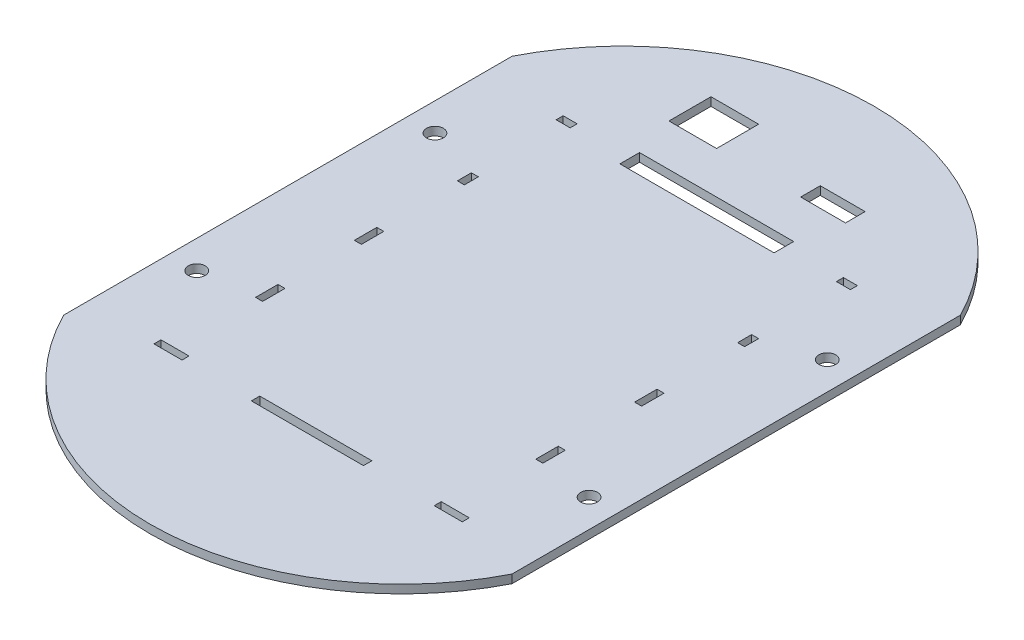
SolidWorks part; units mm, degrees
ref_plane "Front Plane" through (0, 0, 0) normal (0, 0, 1) x (1, 0, 0)
ref_plane "Top Plane" through (0, 0, 0) normal (0, 1, 0) x (1, 0, 0)
ref_plane "Right Plane" through (0, 0, 0) normal (1, 0, 0) x (0, 0, -1)
sketch "Sketch1" plane through (0, 0, 0) normal (0, 1, 0) x (1, 0, 0)
  line L0 (0, 80) -> (191.8529, 80) construction
  line L6 (0, 0) -> (0, 160)
  line L8 (160, 0) -> (160, 160)
  arc A2 (0, 160) -> (160, 160) centre (80, 119.5198) cw
  arc A3 (0, 160) -> (160, 160) centre (80, 160) cw construction
  arc A4 (0, 0) -> (160, 0) centre (80, 40.4802) ccw
  dimension "D3" = 89.6585
  dimension "D1" = 160
  dimension "D2" = 160
extrude "Boss-Extrude1" add sketch "Sketch1" along normal blind 3
sketch "Sketch5" plane through (0, 3, 0) normal (0, 1, 0) x (1, 0, 0)
  line L0 (0, 80) -> (201.3848, 80) construction
  line L1 (0, 160) -> (0, 0) construction
  line L2 (80, 209.1783) -> (80, -99.5859) construction
  circle A0 centre (10, 37.5) radius 3
  arc A1 (160, 160) -> (0, 160) centre (80, 119.5198) ccw construction
  circle A2 centre (150, 37.5) radius 3
  circle A3 centre (150, 122.5) radius 3
  circle A4 centre (10, 122.5) radius 3
  dimension "D1" = 37.5
  dimension "D3" = 6
  dimension "D2" = 10
extrude "Cut-Extrude2" cut sketch "Sketch5" against normal blind 44
sketch "Sketch6" plane through (0, 3, 0) normal (0, 1, 0) x (1, 0, 0)
  line L0 (10, 46.3052) -> (10, 3.8665) construction
  line L1 (150, 150.6243) -> (150, -5.6642) construction
  line L2 (155.6387, 37.5) -> (145.0603, 37.5) construction
  circle A0 centre (9.8857, 144.5) radius 3
  circle A1 centre (9.8857, 122.5) radius 3
  circle A2 centre (10, 122.5) radius 3 construction
  circle A3 centre (150, 122.5) radius 3 construction
  circle A4 centre (10, 37.5) radius 3 construction
  circle A5 centre (150, 122.5) radius 3 construction
  circle A6 centre (10, 37.5) radius 3 construction
  circle A7 centre (10, 15.5) radius 3
  circle A10 centre (150, 144.5) radius 3
  circle A11 centre (150, 15.5) radius 3
  dimension "D1" = 6
  dimension "D2" = 6
  dimension "D5" = 22
  dimension "D6" = 6
  dimension "D7" = 6
  dimension "D10" = 6
  dimension "D3" = 0
  dimension "D4" = 22
  dimension "D8" = 22
  dimension "D9" = 22
sketch "Sketch8" plane through (0, 3, 0) normal (0, 1, 0) x (1, 0, 0)
  line L0 (0, 160) -> (0, 0) construction
  line L1 (52.5, 153) -> (107.5, 153)
  line L2 (52.5, 153) -> (52.5, 146)
  line L3 (52.5, 146) -> (107.5, 146)
  line L4 (107.5, 153) -> (107.5, 146)
  line L5 (52.5, 153) -> (107.5, 146) construction
  line L6 (52.5, 146) -> (107.5, 153) construction
  line L7 (28.75, 39.75) -> (31.25, 39.75)
  line L8 (60, 7) -> (100, 7)
  line L9 (60, 10) -> (100, 10)
  line L10 (100, 10) -> (100, 7)
  line L11 (60, 10) -> (100, 7) construction
  line L12 (60, 7) -> (100, 10) construction
  line L13 (60, 10) -> (60, 7)
  line L14 (30, 222.0853) -> (30, -127.904) construction
  line L15 (27.5, 150.75) -> (32.5, 150.75)
  line L16 (27.5, 150.75) -> (27.5, 148.25)
  line L17 (27.5, 148.25) -> (32.5, 148.25)
  line L18 (32.5, 150.75) -> (32.5, 148.25)
  line L19 (27.5, 150.75) -> (32.5, 148.25) construction
  line L20 (27.5, 148.25) -> (32.5, 150.75) construction
  line L21 (127.5, 150.75) -> (132.5, 150.75)
  line L22 (127.5, 150.75) -> (127.5, 148.25)
  line L23 (127.5, 148.25) -> (132.5, 148.25)
  line L24 (132.5, 150.75) -> (132.5, 148.25)
  line L25 (127.5, 150.75) -> (132.5, 148.25) construction
  line L26 (127.5, 148.25) -> (132.5, 150.75) construction
  line L31 (131.25, 111.75) -> (128.75, 111.75)
  line L32 (131.25, 111.75) -> (131.25, 116.75)
  line L33 (28.75, 116.75) -> (31.25, 116.75)
  line L34 (28.75, 116.75) -> (28.75, 111.75)
  line L35 (28.75, 111.75) -> (31.25, 111.75)
  line L36 (31.25, 116.75) -> (31.25, 111.75)
  line L37 (28.75, 116.75) -> (31.25, 111.75) construction
  line L38 (28.75, 111.75) -> (31.25, 116.75) construction
  line L39 (28.75, 83) -> (31.25, 83)
  line L40 (28.75, 83) -> (28.75, 75)
  line L41 (28.75, 75) -> (31.25, 75)
  line L42 (31.25, 83) -> (31.25, 75)
  line L43 (28.75, 83) -> (31.25, 75) construction
  line L44 (28.75, 75) -> (31.25, 83) construction
  line L49 (131.25, 116.75) -> (128.75, 116.75)
  line L50 (128.75, 111.75) -> (128.75, 116.75)
  line L51 (128.75, 83) -> (131.25, 83)
  line L52 (128.75, 83) -> (128.75, 75)
  line L53 (128.75, 75) -> (131.25, 75)
  line L54 (131.25, 83) -> (131.25, 75)
  line L55 (128.75, 83) -> (131.25, 75) construction
  line L56 (128.75, 75) -> (131.25, 83) construction
  line L57 (25, 7.25) -> (35, 7.25)
  line L58 (25, 7.25) -> (25, 9.75)
  line L59 (25, 9.75) -> (35, 9.75)
  line L60 (35, 7.25) -> (35, 9.75)
  line L61 (25, 7.25) -> (35, 9.75) construction
  line L62 (25, 9.75) -> (35, 7.25) construction
  line L63 (135, 9.75) -> (125, 9.75)
  line L64 (135, 9.75) -> (135, 7.25)
  line L65 (135, 7.25) -> (125, 7.25)
  line L66 (125, 9.75) -> (125, 7.25)
  line L67 (135, 9.75) -> (125, 7.25) construction
  line L68 (135, 7.25) -> (125, 9.75) construction
  line L69 (131.25, 111.75) -> (128.75, 116.75) construction
  line L70 (131.25, 116.75) -> (128.75, 111.75) construction
  line L71 (130, 241.7213) -> (130, -125.654) construction
  line L72 (28.75, 47.75) -> (31.25, 39.75) construction
  line L73 (28.75, 47.75) -> (28.75, 39.75)
  line L74 (128.75, 47.75) -> (131.25, 47.75)
  line L75 (31.25, 47.75) -> (31.25, 39.75)
  line L76 (128.75, 47.75) -> (131.25, 39.75) construction
  line L77 (128.75, 47.75) -> (128.75, 39.75)
  line L78 (28.75, 47.75) -> (31.25, 47.75)
  line L79 (128.75, 39.75) -> (131.25, 39.75)
  line L80 (28.75, 39.75) -> (31.25, 47.75) construction
  line L81 (131.25, 47.75) -> (131.25, 39.75)
  line L82 (128.75, 39.75) -> (131.25, 47.75) construction
  point P0 (80, 149.5)
  point P5 (80, 8.5)
  point P14 (30, 149.5)
  point P19 (130, 149.5)
  point P24 (130, 114.25)
  point P29 (30, 114.25)
  point P34 (30, 79)
  point P43 (30, 43.75)
  point P44 (130, 79)
  point P49 (30, 8.5)
  point P54 (130, 8.5)
  point P63 (130, 43.75)
  dimension "D1" = 80
  dimension "D2" = 55
  dimension "D3" = 7
  dimension "D4" = 7
  dimension "D5" = 7
  dimension "D6" = 40
  dimension "D7" = 3
  dimension "D8" = 80
  dimension "D9" = 2.5
  dimension "D10" = 2.5
  dimension "D11" = 2.5
  dimension "D12" = 2.5
  dimension "D13" = 2.5
  dimension "D14" = 2.5
  dimension "D15" = 2.5
  dimension "D16" = 2.5
  dimension "D17" = 5
  dimension "D18" = 5
  dimension "D19" = 5
  dimension "D20" = 5
  dimension "D21" = 8
  dimension "D22" = 8
  dimension "D23" = 10
  dimension "D24" = 10
  dimension "D25" = 100
  dimension "D26" = 50
  dimension "D27" = 35.25
  dimension "D28" = 35.25
  dimension "D29" = 35.25
  dimension "D30" = 35.25
  dimension "D31" = 8
  dimension "D32" = 8
  dimension "D33" = 35.25
  dimension "D34" = 2.5
  dimension "D35" = 35.25
extrude "Cut-Extrude5" cut sketch "Sketch8" against normal blind 31
sketch "Sketch9" plane through (0, 3, 0) normal (0, 1, 0) x (1, 0, 0)
  line L0 (80, 220.1296) -> (80, 132.7595) construction
  line L1 (48, 183) -> (65, 183)
  line L2 (48, 183) -> (48, 168)
  line L3 (48, 168) -> (65, 168)
  line L4 (65, 183) -> (65, 168)
  line L5 (95, 175) -> (111, 175)
  line L6 (95, 175) -> (95, 168)
  line L7 (95, 168) -> (111, 168)
  line L8 (111, 175) -> (111, 168)
  line L9 (0, 160) -> (0, 0) construction
  line L10 (107.5, 153) -> (52.5, 153) construction
  point P12 (95, 171.5)
  dimension "D1" = 17
  dimension "D2" = 15
  dimension "D3" = 16
  dimension "D4" = 7
  dimension "D5" = 80
  dimension "D6" = 15
  dimension "D7" = 15
  dimension "D8" = 15
  dimension "D9" = 15
extrude "Cut-Extrude6" cut sketch "Sketch9" against normal blind 29
